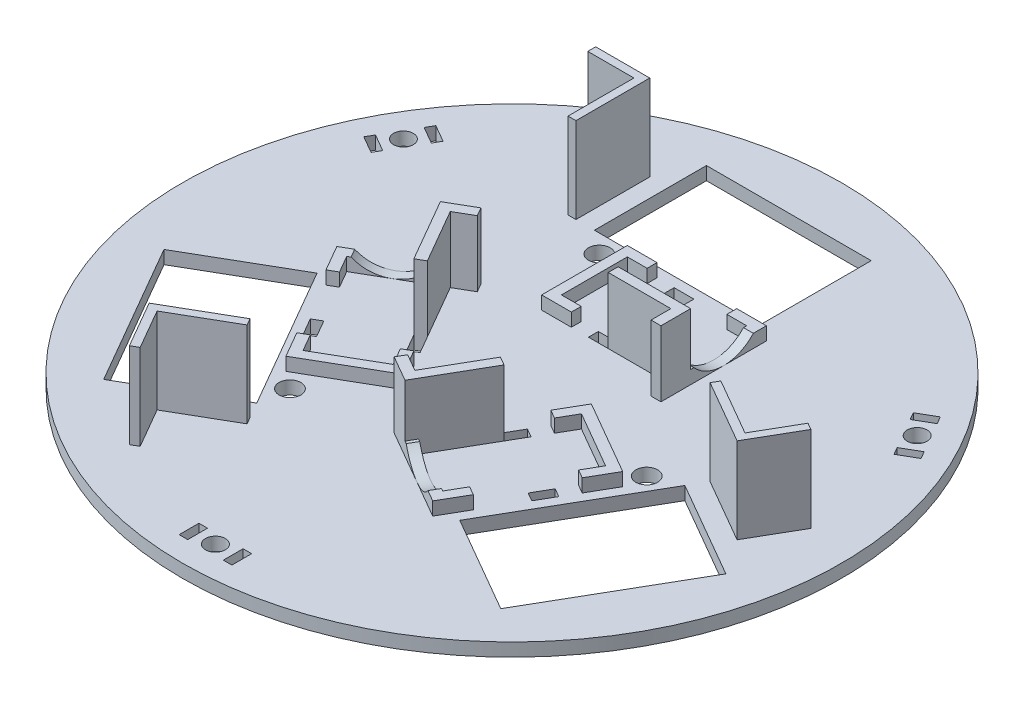
SolidWorks part; units mm, degrees
ref_plane "前视基准面" through (0, 0, 0) normal (0, 0, 1) x (1, 0, 0)
ref_plane "上视基准面" through (0, 0, 0) normal (0, 1, 0) x (1, 0, 0)
ref_plane "右视基准面" through (0, 0, 0) normal (1, 0, 0) x (0, 0, -1)
sketch "草图1" plane through (0, 0, 0) normal (0, 1, 0) x (1, 0, 0)
  line L0 (0, 0) -> (0, 50) construction
  line L1 (-43.3013, -25) -> (0, 0) construction
  line L2 (43.3013, -25) -> (0, 0) construction
  line L3 (42.6231, -10.1747) -> (27.9006, -1.6747)
  line L4 (-12.5, 42) -> (12.5, 42)
  line L5 (-12.5, 42) -> (-12.5, 25)
  line L6 (-12.5, 25) -> (12.5, 25)
  line L7 (12.5, 42) -> (12.5, 25)
  line L8 (42.6231, -10.1747) -> (30.1231, -31.8253)
  line L9 (30.1231, -31.8253) -> (15.4006, -23.3253)
  line L10 (27.9006, -1.6747) -> (15.4006, -23.3253)
  line L11 (-30.1231, -31.8253) -> (-15.4006, -23.3253)
  line L12 (-30.1231, -31.8253) -> (-42.6231, -10.1747)
  line L13 (-42.6231, -10.1747) -> (-27.9006, -1.6747)
  line L14 (-15.4006, -23.3253) -> (-27.9006, -1.6747)
  circle A0 centre (0, 0) radius 50
  point P10 (0, 42)
  point P22 (0, 0)
  dimension "D1" = 100
  dimension "D2" = 120
  dimension "D3" = 120
  dimension "D4" = 17
  dimension "D5" = 25
  dimension "D6" = 8
  dimension "D7" = 3
extrude "凸台-拉伸1" add sketch "草图1" against normal blind 2
sketch "草图2" plane through (0, 0, 0) normal (0, 1, 0) x (1, 0, 0)
  line L0 (0, 12) -> (0, 22) construction
  line L1 (-4.5, 22) -> (13.6, 22)
  line L2 (-4.5, 22) -> (-4.5, 12)
  line L3 (-4.5, 12) -> (13.6, 12)
  line L4 (13.6, 22) -> (13.6, 12)
  line L5 (-12.5, 25) -> (12.5, 25) construction
  line L6 (-6, 23.5) -> (-6, 10.5)
  line L7 (-6, 10.5) -> (15.1, 10.5)
  line L8 (15.1, 23.5) -> (15.1, 10.5)
  line L9 (-6, 23.5) -> (15.1, 23.5)
  line L10 (-1.5, 23.5) -> (-1.5, 10.5)
  line L11 (10.6, 23.5) -> (10.6, 10.5)
  point P8 (0, 25)
  dimension "D1" = 4.5
  dimension "D2" = 18.1
  dimension "D3" = 10
  dimension "D4" = 3
  dimension "D6" = 3
  dimension "D7" = 3
  dimension "D5" = 1.5
extrude "凸台-拉伸2" add sketch "草图2" along normal blind 2 contours L9 L11 L1 L4 L3 L7 L8 | L10 L9 L6 L7 L3 L2 L1
sketch "草图3" plane through (15.1, 0, 0) normal (1, 0, 0) x (0, 0, -1)
  line L0 (23.5, 0) -> (10.5, 0) construction
  line L1 (23.5, 2) -> (10.5, 2) construction
  circle A0 centre (17, 6.1) radius 6.1
  point P6 (17, 2)
  dimension "D1" = 12.2
extrude "切除-拉伸1" cut sketch "草图3" against normal blind 3
sketch "草图4" plane through (0, 0, 0) normal (0, 1, 0) x (1, 0, 0)
  line L0 (-1.5, 23.5) -> (-1.5, 22) construction
  line L1 (1.1, 22) -> (4.1, 22)
  line L2 (1.1, 22) -> (1.1, 23.5)
  line L3 (1.1, 23.5) -> (4.1, 23.5)
  line L4 (4.1, 22) -> (4.1, 23.5)
  line L6 (-4.5, 22) -> (-1.5, 22) construction
  line L7 (-6, 23.5) -> (-1.5, 23.5) construction
  line L8 (10.6, 23.5) -> (10.6, 22) construction
  line L9 (-4.5, 17) -> (13.6, 17) construction
  line L10 (-4.5, 22) -> (-4.5, 12) construction
  line L11 (1.1, 10.5) -> (4.1, 10.5)
  line L12 (4.1, 12) -> (4.1, 10.5)
  line L13 (1.1, 12) -> (4.1, 12)
  line L14 (1.1, 12) -> (1.1, 10.5)
  point P10 (4.1, 22.75)
  point P13 (10.6, 22.75)
  dimension "D1" = 2.6
  dimension "D2" = 6.5
extrude "切除-拉伸2" cut sketch "草图4" against normal blind 3
pattern_circular "阵列(圆周)2" count 3 every 120 about axis through (0, 0, 0) along (0, 1, 0) of "切除-拉伸2", "切除-拉伸1", "凸台-拉伸2"
sketch "草图5" plane through (0, 0, 0) normal (0, 1, 0) x (1, 0, 0)
  line L0 (0, 0) -> (0, -50) construction
  line L1 (-2.7, -43.5) -> (-2.7, -46.5)
  line L2 (-4, -43.5) -> (-2.7, -43.5)
  line L3 (-4, -43.5) -> (-4, -46.5)
  line L4 (-4, -46.5) -> (-2.7, -46.5)
  line L5 (4, -43.5) -> (4, -46.5)
  line L6 (-4, -43.5) -> (-2.7, -43.9875) construction
  line L7 (-4, -46.5) -> (-2.7, -46.0125) construction
  line L8 (2.7, -43.5) -> (2.7, -46.5)
  line L9 (2.7, -43.5) -> (4, -43.5)
  line L10 (-1.4045, -44.4733) -> (1.4045, -45.5267) construction
  line L11 (-1.4045, -45.5267) -> (1.4045, -44.4733) construction
  line L12 (2.7, -46.5) -> (4, -46.5)
  line L13 (2.7, -46.0125) -> (4, -46.5) construction
  line L14 (2.7, -43.9875) -> (4, -43.5) construction
  circle A0 centre (0, -45) radius 1.5
  circle A1 centre (0, 0) radius 50 construction
  dimension "D1" = 3
  dimension "D2" = 45
  dimension "D3" = 1.3
  dimension "D4" = 1.3
  dimension "D5" = 8
extrude "切除-拉伸3" cut sketch "草图5" against normal blind 3
pattern_circular "阵列(圆周)3" count 3 every 120 about axis through (0, 0, 0) along (0, 1, 0) of "切除-拉伸3"
sketch "草图8" plane through (0, 0, 0) normal (0, 1, 0) x (1, 0, 0)
  line L0 (10.6, 10.5) -> (15.1, 10.5) construction
  line L1 (4.1, 12) -> (15.1, 12)
  line L2 (4.1, 12) -> (4.1, 10.5)
  line L3 (4.1, 10.5) -> (13.6, 10.5)
  line L4 (15.1, 12) -> (15.1, 10.5)
  line L6 (15.1, 10.5) -> (15.1, 7.5)
  line L7 (15.1, 7.5) -> (13.6, 7.5)
  line L8 (13.6, 10.5) -> (13.6, 7.5)
  dimension "D1" = 3
extrude "凸台-拉伸3" add sketch "草图8" along normal blind 10
pattern_circular "阵列(圆周)6" count 3 every 120 about axis through (0, 0, 0) along (0, 1, 0) of "凸台-拉伸3"
sketch "草图9" plane through (0, 0, 0) normal (0, 1, 0) x (1, 0, 0)
  line L0 (-16.5, 35) -> (-16.5, 25)
  line L1 (-16.5, 25) -> (-15.3, 25)
  line L2 (-15.3, 25) -> (-15.3, 36.2)
  line L4 (-12.5, 42) -> (-12.5, 25) construction
  line L6 (-12.5, 25) -> (12.5, 25) construction
  line L8 (-15.3, 36.2) -> (-23.5, 36.2)
  line L9 (-23.5, 36.2) -> (-23.5, 35)
  line L10 (-23.5, 35) -> (-16.5, 35)
  line L11 (12.5, 42) -> (-12.5, 42) construction
  dimension "D1" = 4
  dimension "D2" = 1.2
  dimension "D3" = 7
  dimension "D4" = 7
extrude "凸台-拉伸4" add sketch "草图9" along normal blind 13
pattern_circular "阵列(圆周)7" count 3 every 120 about axis through (0, 0, 0) along (0, 1, 0) of "凸台-拉伸4"
sketch "草图10" plane through (0, 0, 0) normal (0, 1, 0) x (1, 0, 0)
  line L0 (23.3516, -6.5538) -> (12.0933, -0.0538) construction
  circle A0 centre (23.7678, -3.3301) radius 1.65
  dimension "D1" = 3.3
  dimension "D2" = 24
  dimension "D3" = 3
extrude "切除-拉伸4" cut sketch "草图10" against normal blind 8
pattern_circular "阵列(圆周)8" count 3 every 120 about axis through (0, 0, 0) along (0, 1, 0) of "切除-拉伸4"
